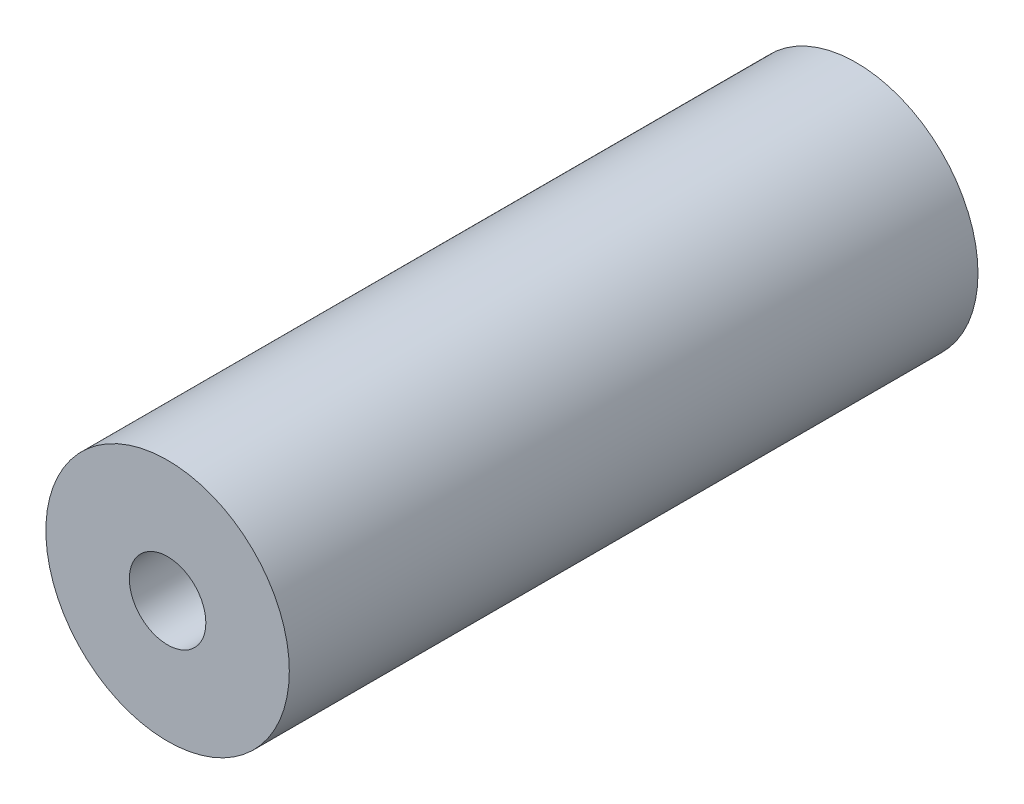
SolidWorks part; units mm, degrees
ref_plane "Front Plane" through (0, 0, 0) normal (0, 0, 1) x (1, 0, 0)
ref_plane "Top Plane" through (0, 0, 0) normal (0, 1, 0) x (1, 0, 0)
ref_plane "Right Plane" through (0, 0, 0) normal (1, 0, 0) x (0, 0, -1)
sketch "Sketch1" plane through (0, 0, 0) normal (0, 0, 1) x (1, 0, 0)
  circle A0 centre (0, 0) radius 17.5
  dimension "D1" = 35
extrude "Boss-Extrude1" add sketch "Sketch1" along normal blind 99
sketch "Sketch3" plane through (0, 0, 99) normal (0, 0, 1) x (1, 0, 0)
  circle A0 centre (0, 0) radius 5.5
  dimension "D1" = 11
extrude "Cut-Extrude2" cut sketch "Sketch3" against normal through all
